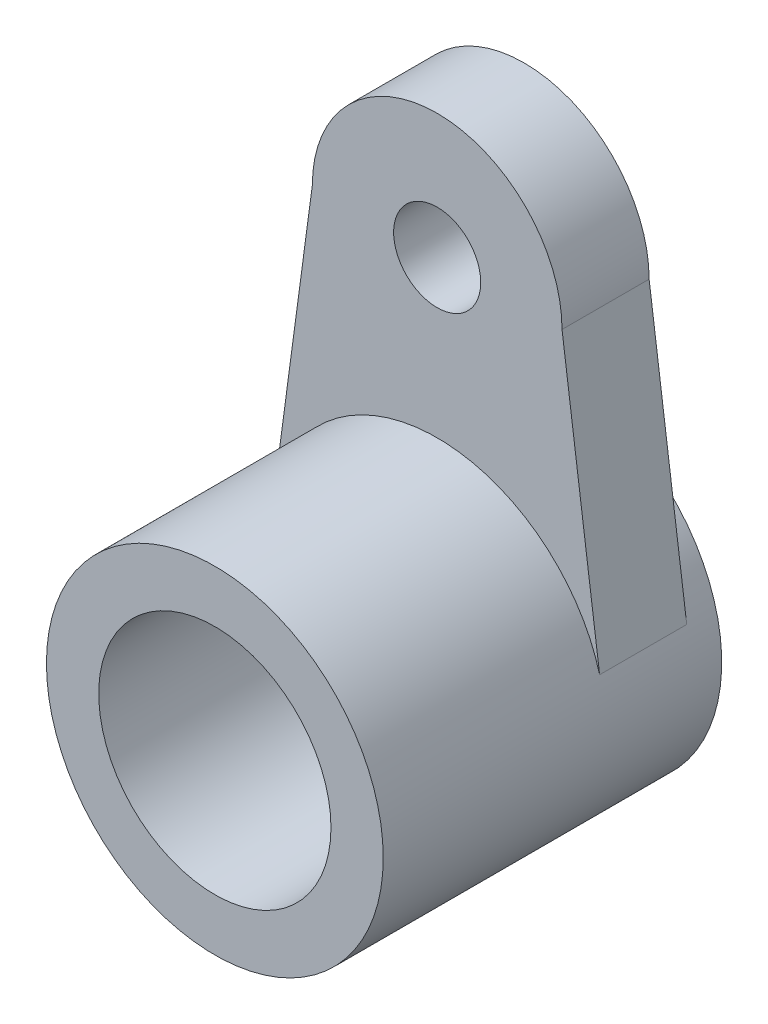
SolidWorks part; units mm, degrees
ref_plane "前视基准面" through (0, 0, 0) normal (0, 0, 1) x (1, 0, 0)
ref_plane "上视基准面" through (0, 0, 0) normal (0, 1, 0) x (1, 0, 0)
ref_plane "右视基准面" through (0, 0, 0) normal (1, 0, 0) x (0, 0, -1)
other "Configuration Table"
sketch "草图1" plane through (0, 0, 0) normal (0, 0, 1) x (1, 0, 0)
  line L1 (-2.15, 0) -> (-2.7974, -4.8256)
  line L2 (2.15, 0) -> (2.7974, -4.8256)
  arc A0 (2.15, 0) -> (-2.15, 0) centre (0, 0) ccw
  arc A1 (-2.7974, -4.8256) -> (2.7974, -4.8256) centre (0, -5.59) ccw
extrude "凸台-拉伸1" add sketch "草图1" along normal blind 1.5
sketch "草图3" plane through (0, 0, 1.5) normal (0, 0, 1) x (1, 0, 0)
  circle A0 centre (0, -5.59) radius 2.9
extrude "凸台-拉伸2" add sketch "草图3" along normal blind 3.829
sketch "草图4" plane through (0, 0, 0) normal (0, 0, -1) x (-1, 0, 0)
  circle A0 centre (0, -5.59) radius 2.9
extrude "凸台-拉伸3" add sketch "草图4" along normal blind 0.5
sketch "草图5" plane through (0, 0, 5.329) normal (0, 0, 1) x (1, 0, 0)
  circle A0 centre (0, -5.59) radius 2
extrude "切除-拉伸1" cut sketch "草图5" against normal blind 3
sketch "草图6" plane through (0, 0, -0.5) normal (0, 0, -1) x (-1, 0, 0)
  circle A0 centre (0, -5.59) radius 2
extrude "切除-拉伸2" cut sketch "草图6" against normal blind 0.7
sketch "草图7" plane through (0, 0, 0.2) normal (0, 0, -1) x (-1, 0, 0)
  circle A0 centre (0, -5.59) radius 1.1
extrude "切除-拉伸3" cut sketch "草图7" against normal blind 3.7
sketch "草图8" plane through (0, 0, 1.5) normal (0, 0, 1) x (1, 0, 0)
  circle A0 centre (0, 0) radius 0.75
extrude "切除-拉伸4" cut sketch "草图8" against normal blind 3.7
